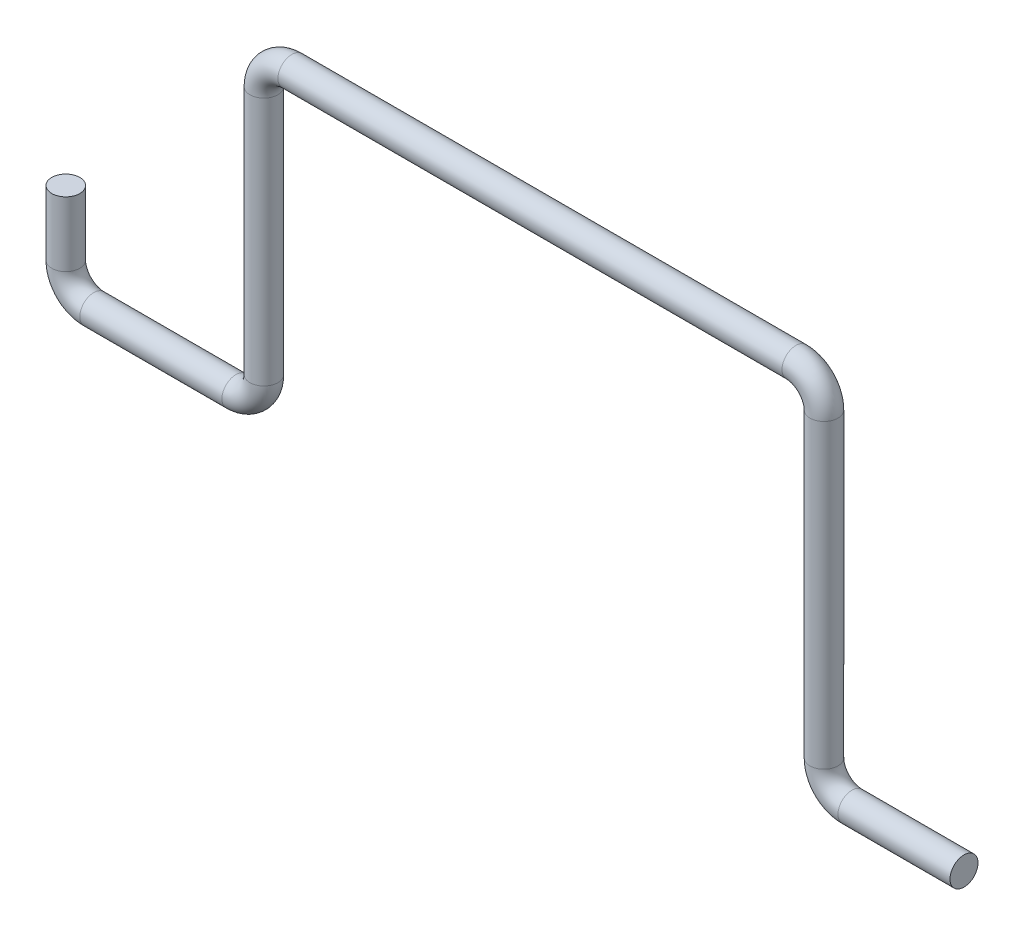
SolidWorks part; units mm, degrees
ref_plane "Front Plane" through (0, 0, 0) normal (0, 0, 1) x (1, 0, 0)
ref_plane "Top Plane" through (0, 0, 0) normal (0, 1, 0) x (1, 0, 0)
ref_plane "Right Plane" through (0, 0, 0) normal (1, 0, 0) x (0, 0, -1)
sketch "Sketch2" plane through (0, 0, 0) normal (1, 0, 0) x (0, 0, -1)
  circle A0 centre (0, 0) radius 0.1
  dimension "D1" = 0.2
sketch3d "3DSketch1"
  line L0 (0, 0, 0) -> (-0.8, 0, 0)
  line L1 (-1, 0.2, 0) -> (-1, 2.351, 0)
  line L2 (-1.2, 2.551, 0) -> (-4.8, 2.551, 0)
  line L3 (-5, 2.351, 0) -> (-5, 0.5703, 0)
  line L4 (-5.2, 0.3703, 0) -> (-6.215, 0.3703, 0)
  line L5 (-6.415, 0.5703, 0) -> (-6.415, 1.0327, 0)
  arc A0 (-0.8, 0, 0) -> (-1, 0.2, 0) centre (-0.8, 0.2, 0) ccw
  arc A1 (-1, 2.351, 0) -> (-1.2, 2.551, 0) centre (-1.2, 2.351, 0) ccw
  arc A2 (-4.8, 2.551, 0) -> (-5, 2.351, 0) centre (-4.8, 2.351, 0) ccw
  arc A3 (-5, 0.5703, 0) -> (-5.2, 0.3703, 0) centre (-5.2, 0.5703, 0) ccw
  arc A4 (-6.215, 0.3703, 0) -> (-6.415, 0.5703, 0) centre (-6.215, 0.5703, 0) ccw
  point P10 (-1, 0, 0)
  point P11 (-0.8, 0.2, -0.2)
  point P14 (-1, 2.551, 0)
  point P15 (-1.2, 2.351, 0.2)
  point P18 (-5, 2.551, 0)
  point P19 (-4.8, 2.351, 0.2)
  point P22 (-5, 0.3703, 0)
  point P23 (-5.2, 0.5703, -0.2)
  point P26 (-6.415, 0.3703, 0)
  point P27 (-6.215, 0.5703, -0.2)
  dimension "D1" = 0.2
sweep "Sweep1" add profiles "Sketch2" path "3DSketch1"
